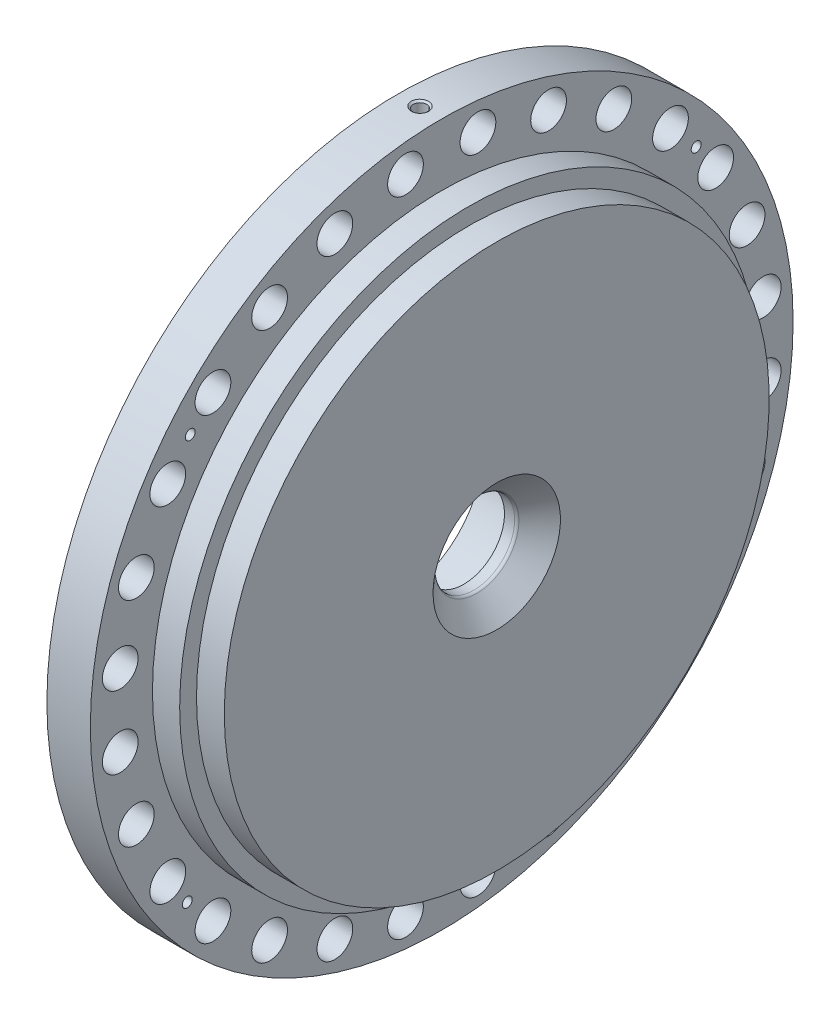
SolidWorks part; units mm, degrees
material "CD4Mc-U Duplex Stainless Steel"
ref_plane "Front Plane" through (0, 0, 0) normal (0, 0, 1) x (1, 0, 0)
ref_plane "Top Plane" through (0, 0, 0) normal (0, 1, 0) x (1, 0, 0)
ref_plane "Right Plane" through (0, 0, 0) normal (1, 0, 0) x (0, 0, -1)
sketch "Sketch1" plane through (0, 0, 0) normal (0, 0, 1) x (1, 0, 0)
  line L13 (-5.9944, 67.7545) -> (-5.9944, 180.9496)
  line L14 (-5.9944, 281.051) -> (28.7528, 281.051)
  line L15 (28.7528, 281.051) -> (28.7528, 231.3686)
  line L16 (28.7528, 231.3686) -> (50.5206, 231.3686)
  line L17 (50.5206, 231.3686) -> (50.5206, 217.9066)
  line L18 (50.5206, 217.9066) -> (72.7456, 217.9066)
  line L19 (72.7456, 217.9066) -> (72.7456, 50.9524)
  line L22 (0, 0) -> (159.4613, 0) construction
  line L27 (-5.9944, 228.9937) -> (0, 228.9937)
  line L28 (0, 228.9937) -> (0, 180.9496)
  line L29 (0, 180.9496) -> (-5.9944, 180.9496)
  line L30 (-5.9944, 228.9937) -> (-5.9944, 281.051)
  line L32 (-5.9944, 67.7545) -> (46.4058, 67.7545)
  line L35 (46.4058, 67.7545) -> (46.4058, 32.5628)
  line L36 (46.4058, 32.5628) -> (54.5317, 32.5628)
  line L37 (56.8749, 33.5953) -> (72.7456, 50.9524)
  arc A0 (54.5317, 32.5628) -> (56.8749, 33.5953) centre (54.5317, 35.7378) ccw
  point P18 (55.9308, 32.5628)
  dimension "D10" = 3.175
  dimension "D1" = 78.74
  dimension "D2" = 43.9928
  dimension "D3" = 21.7678
  dimension "D4" = 9.525
  dimension "D5" = 281.051
  dimension "D6" = 228.9937
  dimension "D7" = 231.3686
  dimension "D8" = 217.9066
  dimension "D9" = 180.9496
  dimension "D11" = 5.9944
  dimension "D12" = 32.5628
  dimension "D13" = 52.4002
  dimension "D14" = 67.7545
  dimension "D16" = 50.9524
revolve "Revolve1" add sketch "Sketch1" angle 360 about L22
sketch "Sketch4" plane through (-5.9944, 0, 0) normal (-1, 0, 0) x (0, 0, 1)
  line L0 (0, 0) -> (0, 281.051) construction
  line L1 (0, 0) -> (28.9721, 257.1355) construction
  circle A1 centre (28.9721, 257.1355) radius 14.2875
  circle A2 centre (0, 0) radius 258.7625 construction
  dimension "D2" = 28.575
  dimension "D3" = 517.525
  dimension "D1" = 6.429
extrude "Cut-Extrude1" cut sketch "Sketch4" against normal through all
pattern_circular "CirPattern2" count 28 over 360 about axis through (0, 0, 0) along (1, 0, 0) of "Cut-Extrude1"
sketch "Sketch5" plane through (0, 0, 0) normal (-1, 0, 0) x (0, 0, 1)
  line L0 (0, 0) -> (53.4138, 199.3429) construction
  line L2 (0, 0) -> (0, 281.051) construction
  circle A0 centre (0, 0) radius 206.375 construction
  circle A1 centre (53.4138, 199.3429) radius 9.525
  circle A3 centre (0, 0) radius 281.051 construction
  point P2 (0, 281.051)
  dimension "D1" = 412.75
  dimension "D3" = 19.05
  dimension "D2" = 15
hole_wizard "3/4-10 Tapped Hole1" positions "Sketch7" profile "Sketch8" tap size "3/4-10" standard "ANSI Inch"
sketch "Sketch7" plane through (0, 0, 0) normal (-1, 0, 0) x (0, 0, 1)
  point P0 (53.4138, 199.3429)
sketch "Sketch8" plane through (0, 199.3429, 53.4138) normal (0, 1, 0) x (0, 0, 1)
  line L0 (0, 0) -> (0, 30.4074)
  line L1 (0, 30.4074) -> (8.3337, 25.4)
  line L2 (8.3337, 25.4) -> (8.3337, 1.8263)
  line L3 (8.3337, 1.8263) -> (10.16, 0)
  line L5 (10.16, 0) -> (0, 0)
  line L6 (-8.3337, 1.8263) -> (-10.16, 0) construction
  line L10 (0, 30.4074) -> (-8.3337, 25.4) construction
  line L11 (0, -6.35) -> (0, 107.95) construction
  dimension "Tap Drill Dia." = 16.6675
  dimension "Tap Drill Depth" = 25.4
  dimension "Near C'Sink Dia." = 20.32
  dimension "Near C'Sink Angle" = 90
  dimension "Drill Angle" = 118
cosmetic thread "Hole Thread2" parameters "D1"=12.7, "D2"=19.05
pattern_circular "CirPattern3" count 12 over 360 about axis through (0, 0, 0) along (1, 0, 0) of "3/4-10 Tapped Hole1"
cosmetic thread "Hole Thread3" parameters "D1"=12.7, "D2"=19.05
cosmetic thread "Hole Thread4" parameters "D1"=12.7, "D2"=19.05
cosmetic thread "Hole Thread5" parameters "D1"=12.7, "D2"=19.05
cosmetic thread "Hole Thread6" parameters "D1"=12.7, "D2"=19.05
cosmetic thread "Hole Thread7" parameters "D1"=12.7, "D2"=19.05
cosmetic thread "Hole Thread8" parameters "D1"=12.7, "D2"=19.05
cosmetic thread "Hole Thread9" parameters "D1"=12.7, "D2"=19.05
cosmetic thread "Hole Thread10" parameters "D1"=12.7, "D2"=19.05
cosmetic thread "Hole Thread11" parameters "D1"=12.7, "D2"=19.05
cosmetic thread "Hole Thread12" parameters "D1"=12.7, "D2"=19.05
cosmetic thread "Hole Thread13" parameters "D1"=12.7, "D2"=19.05
sketch "Sketch9" plane through (-5.9944, 0, 0) normal (-1, 0, 0) x (0, 0, 1)
  line L0 (0, 0) -> (0, 94.996) construction
  line L1 (0, 0) -> (67.1723, 67.1723) construction
  circle A0 centre (0, 0) radius 94.996 construction
  circle A1 centre (67.1723, 67.1723) radius 11.1125
  dimension "D1" = 189.992
  dimension "D3" = 22.225
  dimension "D2" = 45
hole_wizard "7/8-9 Tapped Hole1" positions "3DSketch1" profile "Sketch10" tap size "7/8-9" standard "ANSI Inch"
sketch3d "3DSketch1"
  point P0 (-5.9944, 67.1723, 67.1723)
sketch "Sketch10" plane through (-5.9944, 67.1723, 67.1723) normal (0, 1, 0) x (0, 0, 1)
  line L0 (0, 0) -> (0, 31.2422)
  line L1 (0, 31.2422) -> (9.7231, 25.4)
  line L2 (9.7231, 25.4) -> (9.7231, 2.0244)
  line L3 (9.7231, 2.0244) -> (11.7475, 0)
  line L5 (11.7475, 0) -> (0, 0)
  line L6 (-9.7231, 2.0244) -> (-11.7475, 0) construction
  line L10 (0, 31.2422) -> (-9.7231, 25.4) construction
  line L11 (0, -6.35) -> (0, 107.95) construction
  dimension "Tap Drill Dia." = 19.4462
  dimension "Tap Drill Depth" = 25.4
  dimension "Near C'Sink Dia." = 23.495
  dimension "Near C'Sink Angle" = 90
  dimension "Drill Angle" = 118
cosmetic thread "Hole Thread14" parameters "D1"=44.45, "D2"=22.225
pattern_circular "CirPattern4" count 4 over 360 about axis through (0, 0, 0) along (1, 0, 0) of "7/8-9 Tapped Hole1"
cosmetic thread "Hole Thread15" parameters "D1"=44.45, "D2"=22.225
cosmetic thread "Hole Thread16" parameters "D1"=44.45, "D2"=22.225
cosmetic thread "Hole Thread17" parameters "D1"=44.45, "D2"=22.225
sketch "Sketch11" plane through (-5.9944, 0, 0) normal (-1, 0, 0) x (0, 0, 1)
  line L0 (0, 0) -> (201.0962, 162.8445) construction
  line L1 (0, 0) -> (258.7625, 0) construction
  circle A0 centre (0, 0) radius 258.7625 construction
  circle A2 centre (201.0962, 162.8445) radius 4.7625
  dimension "D1" = 517.525
  dimension "D3" = 9.525
  dimension "D2" = 39
hole_wizard "Tap Drill for 3/8-16 Tap1" positions "3DSketch9" profile "Sketch21" hole size "3/8-16" standard "ANSI Inch"
sketch3d "3DSketch9"
  point P0 (-5.9944, 162.8445, 201.0962)
sketch "Sketch21" plane through (-5.9944, 162.8445, 201.0962) normal (0, 1, 0) x (0, 0, 1)
  line L0 (0, 0) -> (0, 43.0247)
  line L1 (0, 43.0247) -> (3.9687, 40.64)
  line L2 (3.9687, 40.64) -> (3.9687, 0.635)
  line L3 (3.9687, 0.635) -> (4.6037, 0)
  line L5 (4.6037, 0) -> (0, 0)
  line L6 (-3.9687, 0.635) -> (-4.6037, 0) construction
  line L10 (0, 43.0247) -> (-3.9688, 40.64) construction
  line L11 (0, -6.35) -> (0, 107.95) construction
  dimension "Hole Dia." = 7.9375
  dimension "Hole Depth" = 40.64
  dimension "Near C'Sink Dia." = 9.2075
  dimension "Near C'Sink Angle" = 90
  dimension "Drill Angle" = 118
ref_plane "Plane2" through (0, 281.051, 0) normal (0, 1, 0) x (1, 0, 0)
sketch "Sketch20" plane through (0, 281.051, 0) normal (0, 1, 0) x (1, 0, 0)
  line L0 (-5.9944, 0) -> (11.3792, 0) construction
  line L1 (-5.9944, 281.051) -> (-5.9944, -281.051) construction
  dimension "D1" = 17.3736
pattern_circular "CirPattern5" count 56 over 360 about axis through (0, 0, 0) along (-1, 0, 0) skipping 1, 2, 3, 4, 5, 6, 7, 8, 9, 10, 11, 12, 13, 14, 15, 17, 18, 19, 20, 21, 22, 23, 24, 25, 26, 27, 29, 30, 31, 32, 33, 34, 35, 36, 37, 38, 39, 40, 41, 42, 43, 45, 46, 47, 48, 49, 50, 51, 52, 53, 54, 55 of "Tap Drill for 3/8-16 Tap1"
hole_wizard "1/2-13 Tapped Hole4" positions "3DSketch8" profile "Sketch19" tap size "1/2-13" standard "ANSI Inch"
sketch3d "3DSketch8"
  point P0 (11.3792, 281.051, 0)
sketch "Sketch19" plane through (11.3792, 281.051, 0) normal (1, 0, 0) x (0, 0, 1)
  line L0 (0, 0) -> (0, 38.2715)
  line L1 (0, 38.2715) -> (5.3581, 35.052)
  line L2 (5.3581, 35.052) -> (5.3581, 1.3651)
  line L3 (5.3581, 1.3651) -> (6.985, 0)
  line L5 (6.985, 0) -> (0, 0)
  line L6 (-5.3581, 1.3651) -> (-6.985, 0) construction
  line L10 (0, 38.2715) -> (-5.3581, 35.052) construction
  line L11 (0, -6.35) -> (0, 107.95) construction
  dimension "Tap Drill Dia." = 10.7163
  dimension "Tap Drill Depth" = 35.052
  dimension "Near C'Sink Dia." = 13.97
  dimension "Near C'Sink Angle" = 100
  dimension "Drill Angle" = 118
cosmetic thread "Hole Thread24" parameters "D1"=25.4, "D2"=12.7
